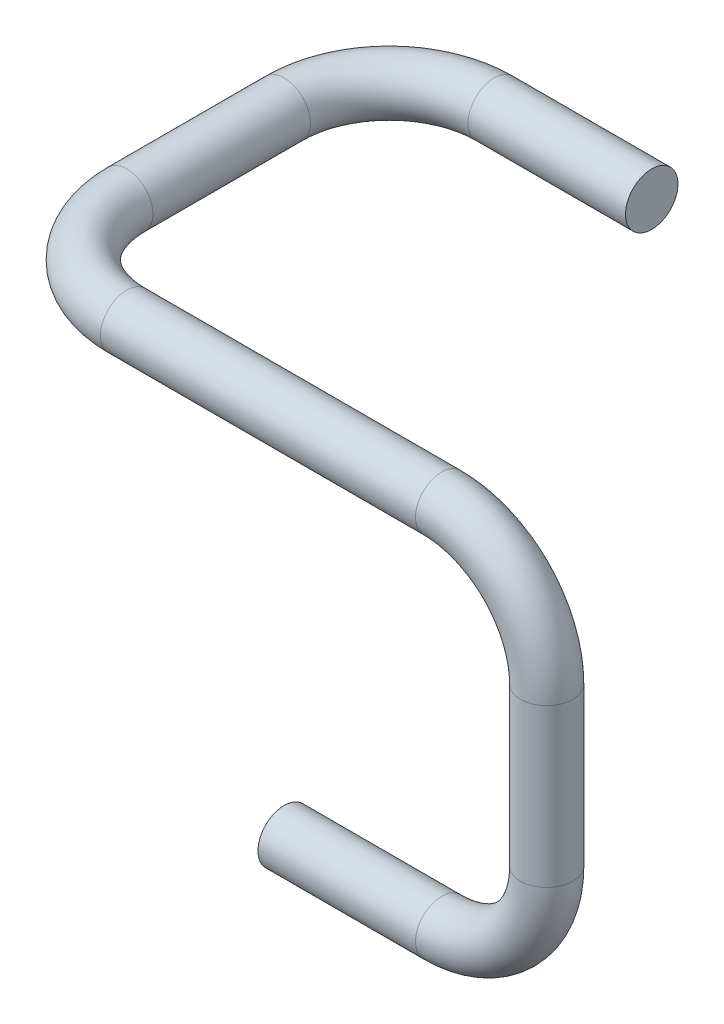
SolidWorks part; units mm, degrees
ref_plane "Front Plane" through (0, 0, 0) normal (0, 0, 1) x (1, 0, 0)
ref_plane "Top Plane" through (0, 0, 0) normal (0, 1, 0) x (1, 0, 0)
ref_plane "Right Plane" through (0, 0, 0) normal (1, 0, 0) x (0, 0, -1)
sketch3d "3DSketch1"
  line L0 (0, 0, -1.5) -> (0, 0, 1.5)
  line L1 (2, 0, -3.5) -> (5, 0, -3.5)
  line L2 (2, 0, 3.5) -> (8, 0, 3.5)
  line L3 (10, -2, 3.5) -> (10, -5, 3.5)
  line L4 (8, -7, 3.5) -> (5, -7, 3.5)
  arc A0 (10, -5, 3.5) -> (8, -7, 3.5) centre (8, -5, 3.5) ccw
  arc A1 (8, 0, 3.5) -> (10, -2, 3.5) centre (8, -2, 3.5) ccw
  arc A2 (0, 0, 1.5) -> (2, 0, 3.5) centre (2, 0, 1.5) ccw
  arc A3 (0, 0, -1.5) -> (2, 0, -3.5) centre (2, 0, -1.5) ccw
  point P9 (10, -7, 3.5)
  point P10 (8, -5, 1.5)
  point P13 (10, 0, 3.5)
  point P14 (8, -2, 1.5)
  point P17 (0, 0, 3.5)
  point P18 (2, 2, 1.5)
  point P21 (0, 0, -3.5)
  point P22 (2, -2, -1.5)
  point P23 (10, -3.5, 3.5)
  dimension "D1" = 2
  dimension "D2" = 7
  dimension "D3" = 10
  dimension "D4" = 7
  dimension "D5" = 5
sweep "Sweep1" add path "3DSketch1" circular profile diameter 1 parameters "D3"=1
